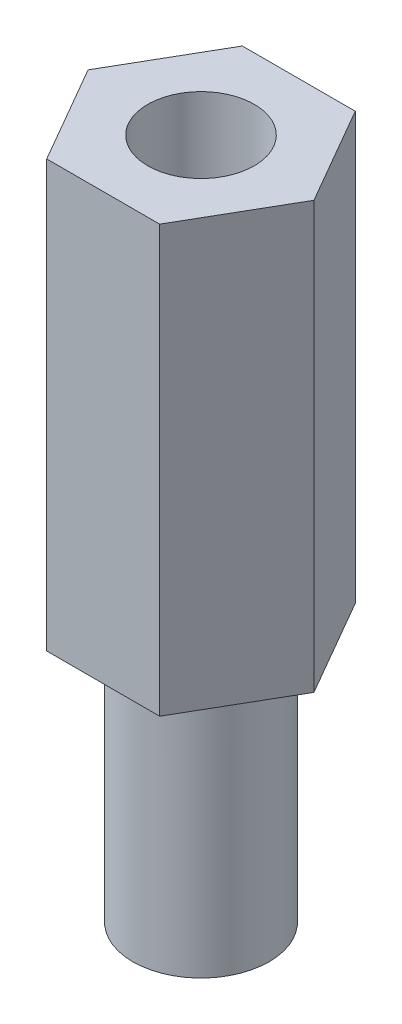
SolidWorks part; units mm, degrees
ref_plane "前视基准面" through (0, 0, 0) normal (0, 0, 1) x (1, 0, 0)
ref_plane "上视基准面" through (0, 0, 0) normal (0, 1, 0) x (1, 0, 0)
ref_plane "右视基准面" through (0, 0, 0) normal (1, 0, 0) x (0, 0, -1)
sketch "草图4" plane through (0, 0, 0) normal (0, 1, 0) x (1, 0, 0)
  line L0 (-12.7945, 0) -> (16.3015, 0) construction
  line L2 (1.325, -2.295) -> (2.65, 0)
  line L3 (2.65, 0) -> (1.325, 2.295)
  line L4 (1.325, 2.295) -> (-1.325, 2.295)
  line L5 (-1.325, 2.295) -> (-2.65, 0)
  line L6 (-2.65, 0) -> (-1.325, -2.295)
  line L7 (-1.325, -2.295) -> (1.325, -2.295)
  circle A0 centre (0, 0) radius 2.295 construction
  dimension "D1" = 5.3
extrude "凸台-拉伸1" add sketch "草图4" along normal blind 10
sketch "草图6" plane through (0, 0, 0) normal (0, -1, 0) x (-1, 0, 0)
  circle A0 centre (0, 0) radius 1.6
  dimension "D1" = 3.2
extrude "凸台-拉伸2" add sketch "草图6" along normal blind 6
cosmetic thread "装饰螺纹线1" parameters "D2"=2.5
sketch "草图7" plane through (0, 10, 0) normal (0, 1, 0) x (1, 0, 0)
  circle A0 centre (0, 0) radius 1.25
  dimension "D1" = 2.5
extrude "切除-拉伸1" cut sketch "草图7" against normal blind 5
cosmetic thread "装饰螺纹线2" parameters "D2"=3
